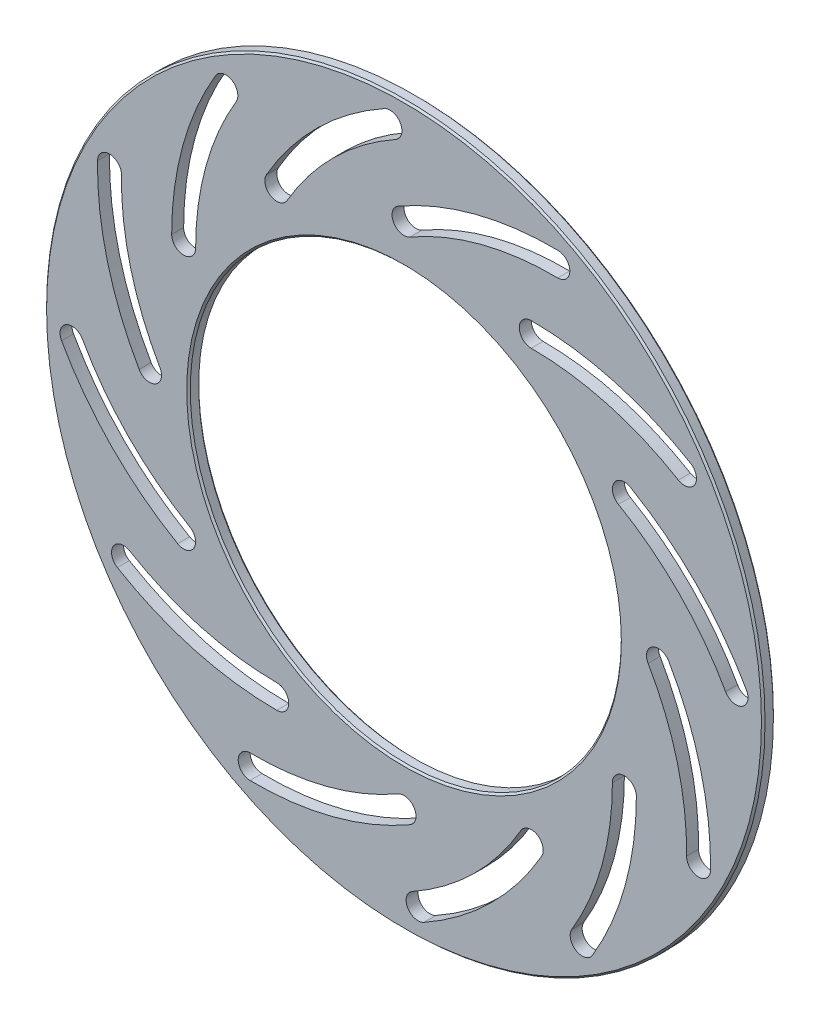
SolidWorks part; units mm, degrees
ref_plane "Front Plane" through (0, 0, 0) normal (0, 0, 1) x (1, 0, 0)
ref_plane "Top Plane" through (0, 0, 0) normal (0, 1, 0) x (1, 0, 0)
ref_plane "Right Plane" through (0, 0, 0) normal (1, 0, 0) x (0, 0, -1)
sketch "Sketch1" plane through (0, 0, 0) normal (0, 0, 1) x (1, 0, 0)
  circle A0 centre (0, 0) radius 36
  circle A1 centre (0, 0) radius 60
  dimension "D1" = 72
  dimension "D2" = 120
extrude "Boss-Extrude1" add sketch "Sketch1" along normal blind 2
sketch "Sketch2" plane through (0, 0, 2) normal (0, 0, 1) x (1, 0, 0)
  line L0 (0, 42.5) -> (0, 55.5) construction
  line L1 (0, 42.5) -> (5.5079, 45.68) construction
  circle A0 centre (0, 0) radius 42.5 construction
  circle A1 centre (0, 0) radius 55.5 construction
  arc A2 (0, 42.5) -> (25.6945, 49.1939) centre (25, -0.8013) cw construction
  arc A7 (25.7223, 51.1937) -> (-1, 44.2321) centre (25, -0.8013) ccw
  arc A8 (25.6668, 47.1941) -> (1, 40.7679) centre (25, -0.8013) ccw
  arc A9 (25.6668, 47.1941) -> (25.7223, 51.1937) centre (25.6945, 49.1939) ccw
  arc A10 (-1, 44.2321) -> (1, 40.7679) centre (0, 42.5) ccw
  point P8 (12.3948, 47.5837)
  dimension "D1" = 85
  dimension "D2" = 111
  dimension "D3" = 50
  dimension "D4" = 2
  dimension "D5" = 60
extrude "Cut-Extrude1" cut sketch "Sketch2" against normal through all
pattern_circular "CirPattern1" count 12 over 360 about axis through (0, 0, 0) along (0, 0, 1) of "Cut-Extrude1"
chamfer "Chamfer1" distance 0.3 angle 45 4 edges at (36, 0, 0) (36, 0, 2) (60, 0, 0) (60, 0, 2)
